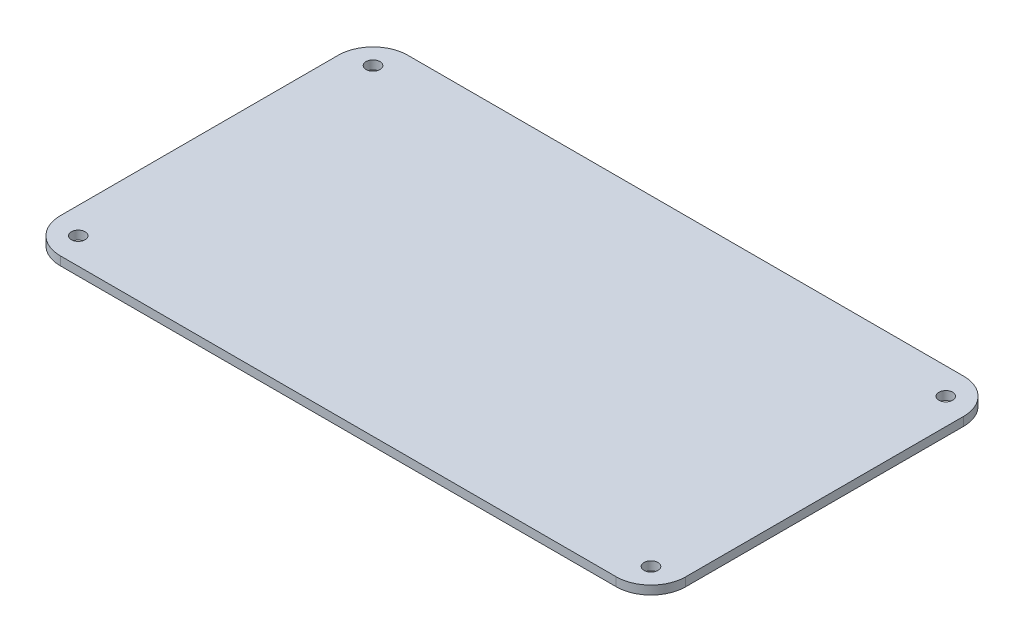
SolidWorks part; units mm, degrees
ref_plane "Front" through (0, 0, 0) normal (0, 0, 1) x (1, 0, 0)
ref_plane "Top" through (0, 0, 0) normal (0, 1, 0) x (1, 0, 0)
ref_plane "Right" through (0, 0, 0) normal (1, 0, 0) x (0, 0, -1)
sketch "Sketch1" plane through (0, 0, 0) normal (0, 1, 0) x (1, 0, 0)
  line L0 (0, -50) -> (0, 50) construction
  line L1 (101.6, -63.5) -> (-101.6, -63.5)
  line L2 (114.3, -50.8) -> (114.3, 50.8)
  line L3 (101.6, 63.5) -> (-101.6, 63.5)
  line L4 (-114.3, -50.8) -> (-114.3, 50.8)
  line L5 (114.3, -63.5) -> (-114.3, 63.5) construction
  line L6 (114.3, 63.5) -> (-114.3, -63.5) construction
  line L7 (-50, 0) -> (50, 0) construction
  arc A0 (-101.6, -63.5) -> (-114.3, -50.8) centre (-101.6, -50.8) cw
  arc A1 (101.6, -63.5) -> (114.3, -50.8) centre (101.6, -50.8) ccw
  arc A2 (114.3, 50.8) -> (101.6, 63.5) centre (101.6, 50.8) ccw
  arc A3 (-101.6, 63.5) -> (-114.3, 50.8) centre (-101.6, 50.8) ccw
  circle A4 centre (-104.6734, 53.8734) radius 2.54
  circle A5 centre (104.6734, 53.8734) radius 2.54
  circle A6 centre (104.6734, -53.8734) radius 2.54
  circle A7 centre (-104.6734, -53.8734) radius 2.54
  point P0 (0, 0)
  dimension "D3" = 12.7
  dimension "D4" = 5.08
  dimension "D5" = 9.6266
  dimension "D1" = 228.6
  dimension "D2" = 127
  dimension "D6" = 9.6266
extrude "Boss-Extrude2" add sketch "Sketch1" along normal blind 3.175
